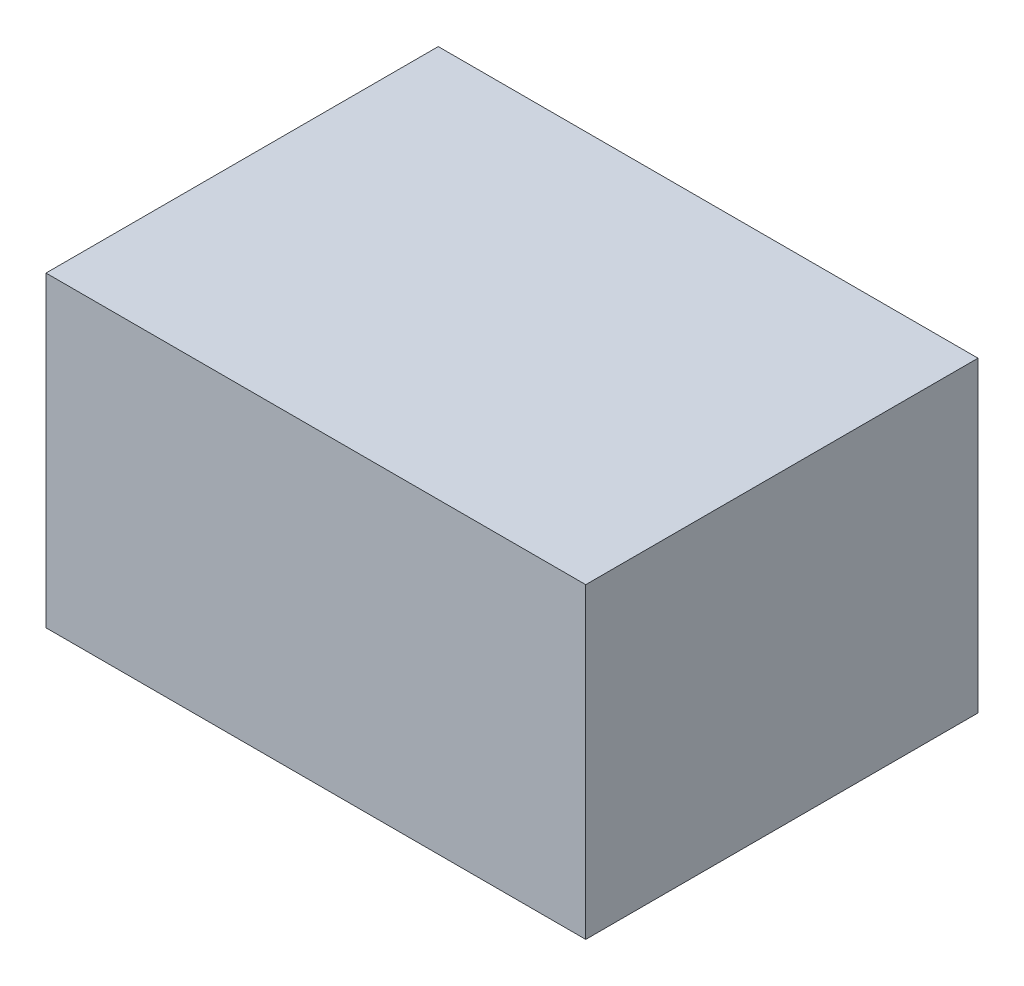
SolidWorks part; units mm, degrees
ref_plane "Front Plane" through (0, 0, 0) normal (0, 0, 1) x (1, 0, 0)
ref_plane "Top Plane" through (0, 0, 0) normal (0, 1, 0) x (1, 0, 0)
ref_plane "Right Plane" through (0, 0, 0) normal (1, 0, 0) x (0, 0, -1)
sketch "Sketch1" plane through (0, 0, 0) normal (0, 0, 1) x (1, 0, 0)
  line L1 (-26.35, -15) -> (26.35, -15)
  line L2 (-26.35, -15) -> (-26.35, 15)
  line L3 (-26.35, 15) -> (26.35, 15)
  line L4 (26.35, -15) -> (26.35, 15)
  line L5 (-26.35, -15) -> (26.35, 15) construction
  line L6 (-26.35, 15) -> (26.35, -15) construction
  point P0 (0, 0)
extrude "Envelope" add sketch "Sketch1" along normal blind 38.3
